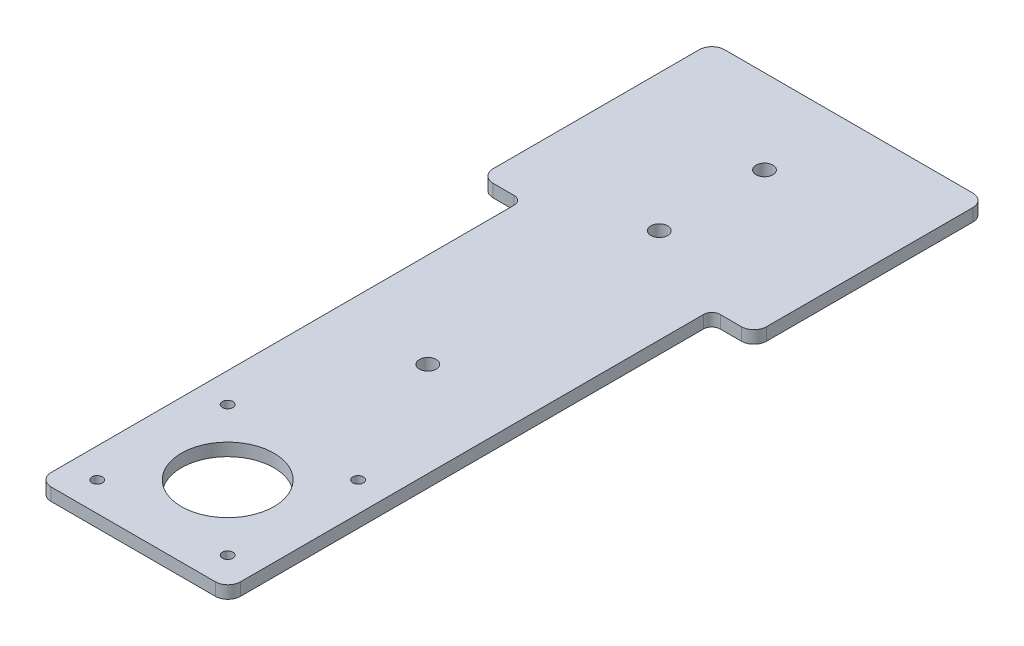
SolidWorks part; units mm, degrees
ref_plane "Front Plane" through (0, 0, 0) normal (0, 0, 1) x (1, 0, 0)
ref_plane "Top Plane" through (0, 0, 0) normal (0, 1, 0) x (1, 0, 0)
ref_plane "Right Plane" through (0, 0, 0) normal (1, 0, 0) x (0, 0, -1)
sketch "Sketch1" plane through (0, 0, 0) normal (0, 1, 0) x (1, 0, 0)
  line L1 (0, 28.9333) -> (0, -58.3864) construction
  line L2 (0, 111.6136) -> (-32.5, 111.6136)
  line L3 (0, 111.6136) -> (32.5, 111.6136)
  line L4 (0, -58.3864) -> (-22.5, -58.3864)
  line L5 (-22.5, -58.3864) -> (0, -58.3864)
  line L6 (0, -58.3864) -> (22.5, -58.3864)
  line L7 (0, 104.294) -> (0, 28.9333) construction
  line L8 (-32.5, 111.6136) -> (-32.5, 56.6136)
  line L9 (32.5, 111.6136) -> (32.5, 56.6136)
  line L10 (-22.5, -58.3864) -> (-22.5, 56.6136)
  line L11 (22.5, -58.3864) -> (22.5, 56.6136)
  line L12 (22.5, 56.6136) -> (32.5, 56.6136)
  line L13 (-32.5, 56.6136) -> (-22.5, 56.6136)
  line L14 (-15.5, -20.454) -> (15.5, -51.454) construction
  line L15 (-15.5, -51.454) -> (15.5, -20.454) construction
  circle A0 centre (0, 91.6136) radius 2
  circle A1 centre (0, 66.6136) radius 2
  circle A2 centre (-15.5, -20.454) radius 1.25
  circle A3 centre (-15.5, -51.454) radius 1.25
  circle A4 centre (15.5, -51.454) radius 1.25
  circle A5 centre (15.5, -20.454) radius 1.25
  circle A6 centre (0, -35.954) radius 11
  circle A7 centre (0, 11.6136) radius 2
  dimension "D10" = 2.5
  dimension "D11" = 2.5
  dimension "D12" = 4
  dimension "D13" = 4
  dimension "D16" = 31
  dimension "D17" = 22
  dimension "D18" = 4
  dimension "D1" = 32.5
  dimension "D2" = 32.5
  dimension "D3" = 22.5
  dimension "D4" = 22.5
  dimension "D5" = 170
  dimension "D6" = 55
  dimension "D7" = 55
  dimension "D8" = 15.5
  dimension "D9" = 15.5
  dimension "D14" = 20
  dimension "D15" = 45
  dimension "D19" = 70
sketch "Sketch2" plane through (0, 0, 0) normal (0, 1, 0) x (1, 0, 0)
extrude "Boss-Extrude1" add sketch "Sketch1" along normal blind 3 contours L8 L13 L10 L4 L6 L11 L12 L9 L3 L2
fillet "Fillet1" radius 3 1 edges at (32.5, 1.5, -111.6136)
fillet "Fillet2" radius 3 1 edges at (-32.5, 1.5, -111.6136)
fillet "Fillet3" radius 3 1 edges at (-32.5, 1.5, -56.6136)
fillet "Fillet4" radius 3 1 edges at (32.5, 1.5, -56.6136)
fillet "Fillet5" radius 3 1 edges at (22.5, 1.5, 58.3864)
fillet "Fillet7" radius 3 1 edges at (-22.5, 1.5, 58.3864)
fillet "Fillet8" radius 2 1 edges at (-22.5, 1.5, -56.6136)
fillet "Fillet9" radius 2 1 edges at (22.5, 1.5, -56.6136)
